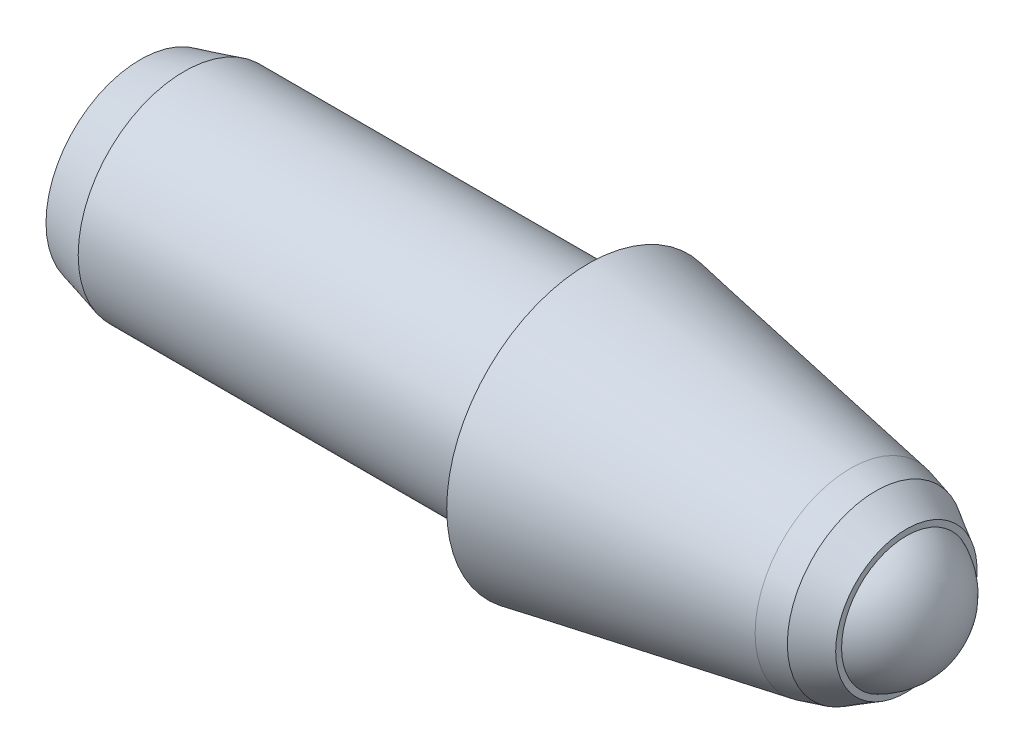
SolidWorks part; units mm, degrees
material "Liga de aço fundido"
ref_plane "Frontal" through (0, 0, 0) normal (0, 0, 1) x (1, 0, 0)
ref_plane "Superior" through (0, 0, 0) normal (0, 1, 0) x (1, 0, 0)
ref_plane "Lateral" through (0, 0, 0) normal (1, 0, 0) x (0, 0, -1)
sketch "Sketch1" plane through (0, 0, 0) normal (0, 0, 1) x (1, 0, 0)
  line L0 (-0.1579, 0) -> (7.8954, 0) construction
  line L1 (0, 0.465) -> (0, 0.8)
  line L2 (3.8, 0.9) -> (0.3732, 0.9)
  line L3 (3.8, 0.9) -> (3.8, 1.2)
  line L4 (3, 0.45) -> (0.615, 0.45)
  line L5 (0.3732, 0.9) -> (0, 0.8)
  line L6 (6.5, 0.5999) -> (6.24, 0.75)
  line L7 (6.24, 0.75) -> (6.5, 0.67) construction
  line L8 (6.5, 0.5999) -> (6.5, 0.5499)
  line L9 (3, 0.45) -> (3.0289, 0.4)
  line L10 (3.8, 1.2) -> (6.0244, 0.8078)
  line L11 (6.0244, 0.8078) -> (6.24, 0.75)
  line L12 (6.26, 0.6) -> (6.0115, 0.6)
  line L13 (3.0289, 0.4) -> (5, 0.4)
  line L14 (5, 0.4) -> (5.0289, 0.35)
  line L15 (6.0115, 0.6) -> (5.7615, 0.35)
  line L18 (0, 0.465) -> (0.6, 0.465)
  line L19 (0.6, 0.465) -> (0.615, 0.45)
  line L25 (6.5, 0.67) -> (6.5, 0.5999) construction
  line L26 (5.7615, 0.35) -> (5.0289, 0.35)
  circle A1 centre (6.26, 0) radius 0.6 construction
  arc A2 (6.5, 0.5499) -> (6.26, 0.6) centre (6.26, 0) ccw
  dimension "D3" = 2.4
  dimension "D11" = 45
  dimension "D21" = 45
  dimension "D16" = 30
  dimension "D15" = 1.2
  dimension "D5" = 1.34
  dimension "D20" = 0.26
  dimension "D13" = 10
  dimension "D6" = 0.3732
  dimension "D28" = 0.465
  dimension "D30" = 0.6
  dimension "D17" = 0.05
  dimension "D12" = 0.36
  dimension "D24" = 6.86
  dimension "D7" = 1.6
  dimension "D8" = 0.9
  dimension "D9" = 2.4
  dimension "D10" = 0.9
  dimension "D14" = 60
  dimension "D18" = 0.8
  dimension "D19" = 5
  dimension "D22" = 15
  dimension "D23" = 3.8
  dimension "D25" = 15
  dimension "D26" = 2.4
  dimension "D27" = 1.5
  dimension "D35" = 3
  dimension "D40" = 2.7
  dimension "D44" = 0.7
revolve "Base-Revolve" add sketch "Sketch1" angle 360 about L0
sketch "Sketch2" plane through (0, 0, 0) normal (0, 0, 1) x (1, 0, 0)
  line L0 (4.9797, 0) -> (7.1999, 0) construction
  line L1 (5.66, 0) -> (6.86, 0)
  line L2 (6.0115, 0.6) -> (5.7615, 0.35) construction
  arc A0 (6.86, 0) -> (5.66, 0) centre (6.26, 0) ccw
  point P8 (6.5772, -0.3708)
  dimension "D2" = 0.6
  dimension "D3" = 0.7416
revolve "Esfera" add sketch "Sketch2" angle 360 about L0
